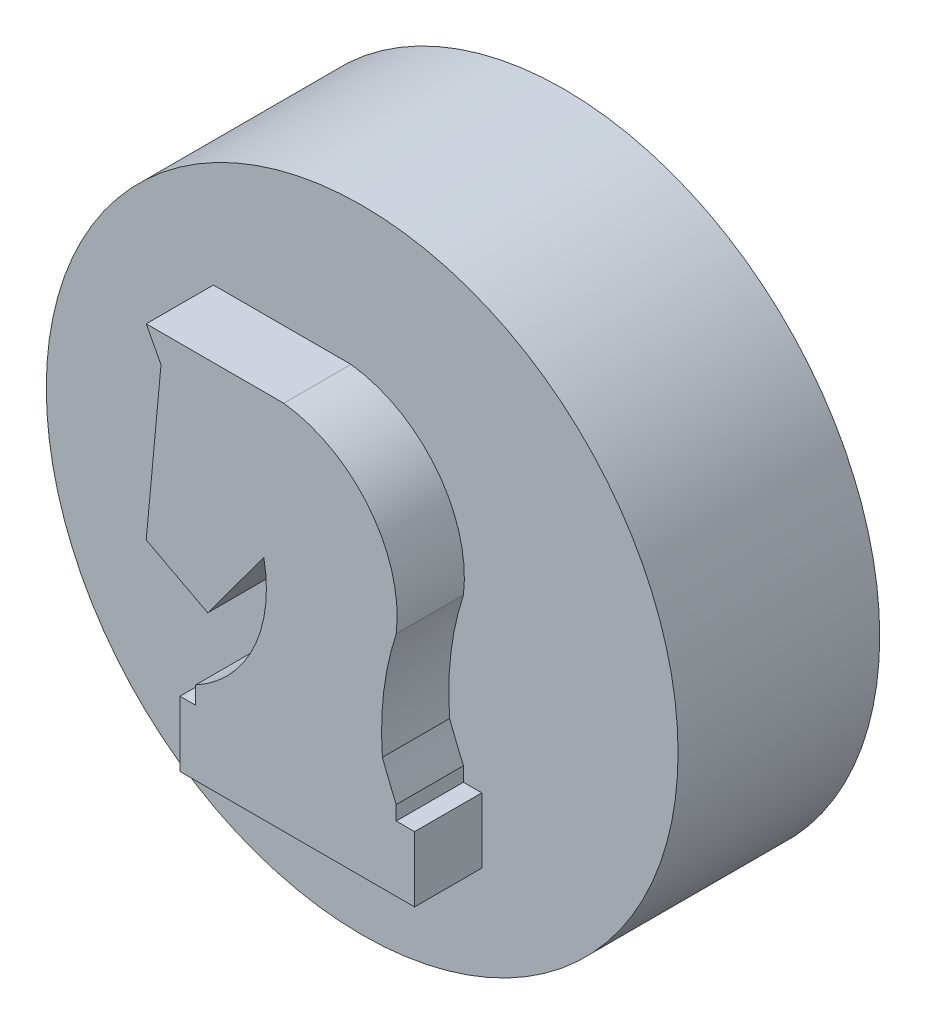
SolidWorks part; units mm, degrees
ref_plane "Front Plane" through (0, 0, 0) normal (0, 0, 1) x (1, 0, 0)
ref_plane "Top Plane" through (0, 0, 0) normal (0, 1, 0) x (1, 0, 0)
ref_plane "Right Plane" through (0, 0, 0) normal (1, 0, 0) x (0, 0, -1)
sketch "Sketch1" plane through (0, 0, 0) normal (0, 0, 1) x (1, 0, 0)
  circle A0 centre (0, 0) radius 8.763
  circle A1 centre (0, 0) radius 11.938
  dimension "D1" = 17.526
  dimension "D2" = 23.876
extrude "Boss-Extrude1" add sketch "Sketch1" along normal blind 5.08
sketch "Sketch2" plane through (0, 0, 5.08) normal (0, 0, 1) x (1, 0, 0)
  circle A0 centre (0, 0) radius 11.938
extrude "Boss-Extrude2" add sketch "Sketch2" along normal blind 2.54
sketch "Sketch3" plane through (0, 0, 7.62) normal (0, 0, 1) x (1, 0, 0)
  line L0 (76.4074, 247.7537) -> (417.7408, 247.7537) construction
  line L1 (0, 0) -> (0, 10.7108) construction
  line L30 (33.3333, 100.0554) -> (166.6667, 100.0554) construction
  line L31 (76.5513, 248.4132) -> (417.8847, 248.4132) construction
  line L50 (33.4547, 119.6194) -> (204.1214, 119.6194) construction
  line L51 (-3.7498, -5.0259) -> (-3.7498, -4.3577)
  line L52 (-4.3442, -7.4903) -> (4.5196, -7.4903)
  line L53 (-4.3442, -7.4903) -> (-4.3442, -5.0259)
  line L54 (-4.3442, -5.0259) -> (-3.7498, -5.0259)
  line L55 (4.5196, -7.4903) -> (4.5196, -5.0259)
  line L56 (-1.1767, 1.1002) -> (-3.2949, -1.7717)
  line L57 (-3.2949, -1.7717) -> (-5.6211, -0.5501)
  line L58 (-5.6211, -0.5501) -> (-5.0623, 5.4627)
  line L59 (-5.0623, 5.4627) -> (-5.6211, 6.5231)
  line L60 (-5.6211, 6.5231) -> (-0.4228, 6.5231)
  line L61 (3.8264, -4.4864) -> (3.8264, -5.0259)
  line L62 (3.8264, -5.0259) -> (4.5196, -5.0259)
  arc A15 (-3.7498, -4.3577) -> (-1.1767, 1.1002) centre (-6.154, 0.1112) ccw
  arc A16 (-0.4228, 6.5231) -> (3.8264, 1.1002) centre (-1.0096, 1.6871) cw
  arc A17 (3.8264, 1.1002) -> (3.3045, -3.2011) centre (14.3582, -2.3601) ccw
  arc A18 (3.3045, -3.2011) -> (3.8264, -4.4864) centre (28.3417, 6.2176) ccw
extrude "Boss-Extrude5" add sketch "Sketch3" along normal blind 2.54
